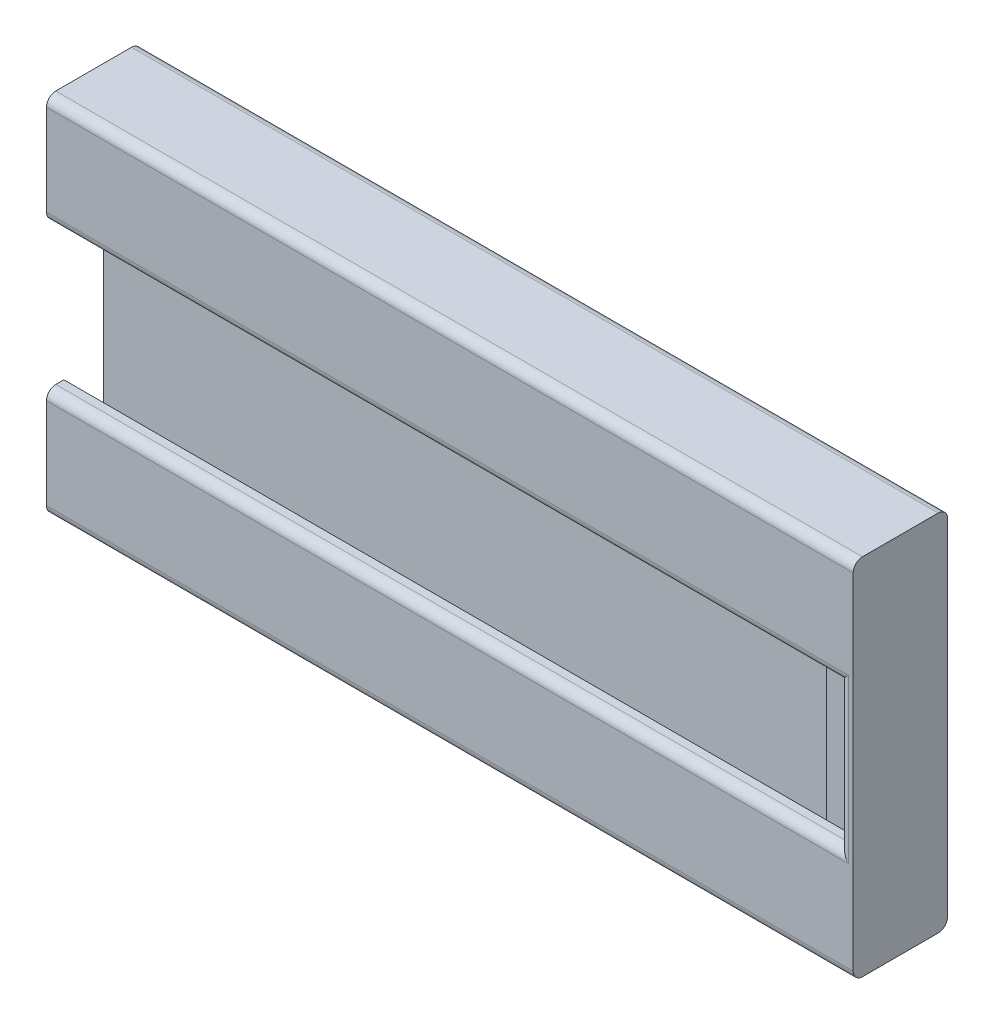
SolidWorks part; units mm, degrees
other "light shade cover"
other "PCB Mount"
ref_plane "Front Plane" through (0, 0, 0) normal (0, 0, 1) x (1, 0, 0)
ref_plane "Top Plane" through (0, 0, 0) normal (0, 1, 0) x (1, 0, 0)
ref_plane "Right Plane" through (0, 0, 0) normal (1, 0, 0) x (0, 0, -1)
sketch "Sketch1" plane through (0, 0, 0) normal (0, 0, 1) x (1, 0, 0)
  line L1 (0, 0) -> (85, 0)
  line L2 (0, 0) -> (0, 35)
  line L3 (0, 35) -> (85, 35)
  line L4 (85, 0) -> (85, 35)
  dimension "D1" = 85
  dimension "D2" = 35
extrude "Boss-Extrude1" add sketch "Sketch1" along normal blind 2
sketch "Sketch2" plane through (0, 0, 2) normal (0, 0, 1) x (1, 0, 0)
  line L0 (85, 0) -> (85, 35) construction
  line L1 (0, 2.125) -> (83, 2.125)
  line L2 (0, 2.125) -> (0, 32.875)
  line L3 (0, 32.875) -> (83, 32.875)
  line L4 (83, 2.125) -> (83, 32.875)
  line L5 (0, 35) -> (0, 0) construction
  line L7 (0, 35) -> (85, 35)
  line L8 (0, 35) -> (0, 0)
  line L9 (0, 0) -> (85, 0)
  line L10 (85, 35) -> (85, 0)
  point P6 (85, 17.5)
  point P7 (83, 17.5)
  line M5 (0, 35) -> (0, 0)
  line M6 (0, 0) -> (85, 0)
  line M7 (85, 0) -> (85, 35)
  line M8 (85, 35) -> (0, 35)
  dimension "D1" = 30.75
  dimension "D2" = 2
extrude "Boss-Extrude2" add sketch "Sketch2" along normal blind 2 contours L4 L1 L3 M5 M6 M7 M8
sketch "Sketch3" plane through (0, 0, 4) normal (0, 0, 1) x (1, 0, 0)
  line L0 (0, 32.875) -> (83, 32.875) construction
  line L1 (0, 0) -> (85, 0)
  line L2 (0, 0) -> (0, 35)
  line L3 (0, 35) -> (85, 35)
  line L4 (85, 0) -> (85, 35)
  line L5 (0, 30.875) -> (81.5, 30.875)
  line L6 (0, 30.875) -> (0, 4.125)
  line L7 (0, 4.125) -> (81.5, 4.125)
  line L8 (81.5, 30.875) -> (81.5, 4.125)
  line L9 (0, 2.125) -> (83, 2.125) construction
  line L11 (83, 2.125) -> (83, 32.875) construction
  line L13 (0, 0) -> (85, 0)
  line L14 (0, 0) -> (0, 35)
  line L15 (0, 35) -> (85, 35)
  line L16 (85, 0) -> (85, 35)
  line M9 (83, 32.875) -> (83, 2.125)
  line M10 (83, 2.125) -> (0, 2.125)
  line M11 (0, 2.125) -> (0, 0)
  line M12 (0, 0) -> (85, 0)
  line M13 (85, 0) -> (85, 35)
  line M14 (85, 35) -> (0, 35)
  line M15 (0, 35) -> (0, 32.875)
  line M16 (0, 32.875) -> (83, 32.875)
  dimension "D1" = 1.5
  dimension "D2" = 2
  dimension "D3" = 2
extrude "Boss-Extrude3" add sketch "Sketch3" along normal blind 2 contours L5 L8 L7 L2 M10 M9 M16 | M16 M9 M10 M11 M12 M13 M14 M15
sketch "Sketch5" plane through (85, 0, 0) normal (1, 0, 0) x (0, 0, -1)
  line L0 (0, 0) -> (0, 35) construction
  line L1 (2, 37) -> (-8.118, 37)
  line L2 (2, 37) -> (2, -2)
  line L3 (2, -2) -> (-8.118, -2)
  line L4 (-8.118, 37) -> (-8.118, -2)
  line L5 (-6, 35) -> (0, 35) construction
  line L6 (-6.25, 25.25) -> (-8.118, 25.25)
  line L7 (-6.25, 35.25) -> (0.25, 35.25)
  line L8 (-6.25, 35.25) -> (-6.25, -0.25)
  line L9 (-6.25, -0.25) -> (0.25, -0.25)
  line L10 (0.25, 35.25) -> (0.25, -0.25)
  line L11 (-6.25, 9.75) -> (-8.118, 9.75)
  point P12 (0, 17.5)
  point P13 (0.25, 17.5)
  point P14 (-3, 35)
  point P15 (-3, 35.25)
  point P20 (2, 17.5)
  dimension "D1" = 2
  dimension "D2" = 2
  dimension "D3" = 0.25
  dimension "D4" = 0.25
  dimension "D5" = 10
  dimension "D6" = 10
extrude "Boss-Extrude4" add sketch "Sketch5" against normal up to surface (85 mm away) separate body contours L8 L11 L4 L3 L2 L1 L6 L7 L10 L9 up to face at (0, 17.5, 3.6667)
sketch "Sketch6" plane through (85, 0, 0) normal (1, 0, 0) x (0, 0, -1)
  line L1 (-8.118, 37) -> (2, 37)
  line L2 (-8.118, 37) -> (-8.118, -2)
  line L3 (-8.118, -2) -> (2, -2)
  line L4 (2, 37) -> (2, -2)
extrude "Boss-Extrude5" add sketch "Sketch6" along normal blind 1.5
fillet "Fillet1" radius 1 7 edges at (85, 17.5, 8.118) (42.5, 25.25, 8.118) (42.5, 9.75, 8.118) (43.25, -2, 8.118) (43.25, -2, -2) (43.25, 37, 8.118) (43.25, 37, -2)
